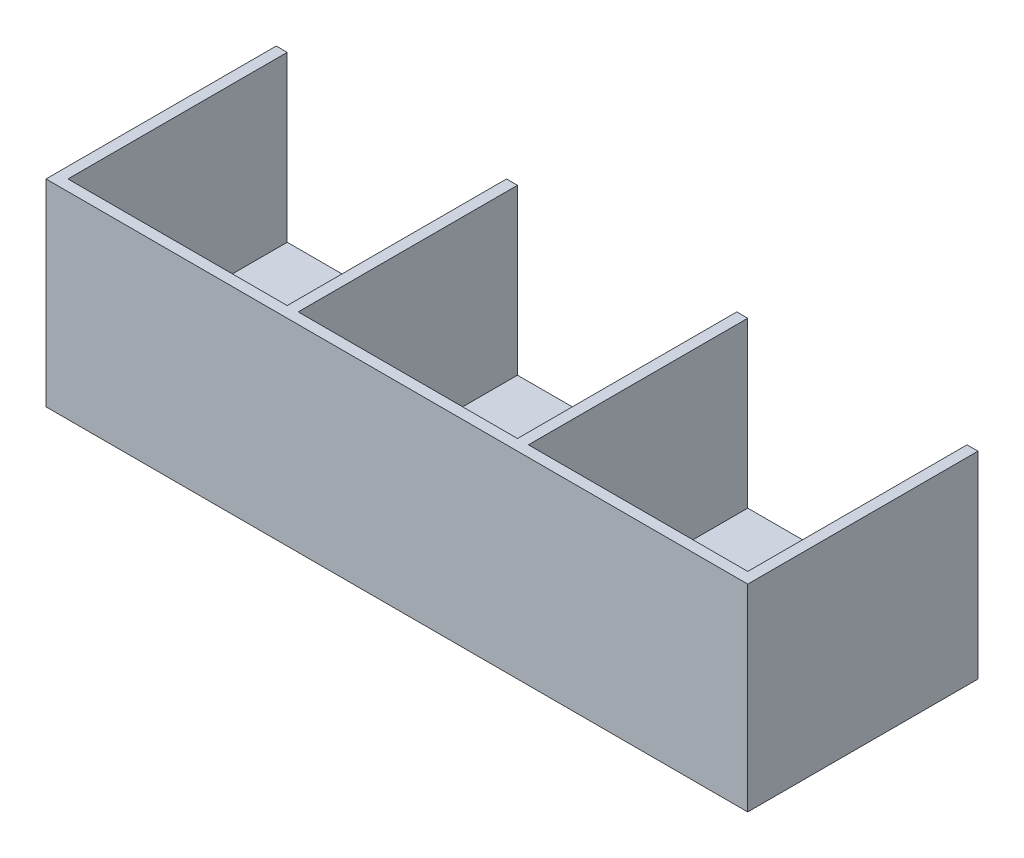
SolidWorks part; units mm, degrees
ref_plane "Alzado" through (0, 0, 0) normal (0, 0, 1) x (1, 0, 0)
ref_plane "Planta" through (0, 0, 0) normal (0, 1, 0) x (1, 0, 0)
ref_plane "Vista lateral" through (0, 0, 0) normal (1, 0, 0) x (0, 0, -1)
sketch "Croquis1" plane through (0, 0, 0) normal (0, 1, 0) x (1, 0, 0)
  line L1 (-320, 110) -> (320, 110)
  line L2 (-320, 110) -> (-320, -110)
  line L3 (-320, -110) -> (320, -110)
  line L4 (320, 110) -> (320, -110)
  line L5 (-310, 100) -> (-110, 100)
  line L6 (-310, 100) -> (-310, -100)
  line L7 (-310, -100) -> (-110, -100)
  line L8 (-110, 100) -> (-110, -100)
  line L9 (-100, 100) -> (100, 100)
  line L10 (-100, 100) -> (-100, -100)
  line L11 (-100, -100) -> (100, -100)
  line L12 (100, 100) -> (100, -100)
  line L13 (110, 100) -> (310, 100)
  line L14 (110, 100) -> (110, -100)
  line L15 (110, -100) -> (310, -100)
  line L16 (310, 100) -> (310, -100)
  point P0 (0, 0)
  dimension "D1" = 640
  dimension "D2" = 220
  dimension "D3" = 200
  dimension "D4" = 200
  dimension "D5" = 200
  dimension "D6" = 10
  dimension "D7" = 10
  dimension "D8" = 10
  dimension "D9" = 10
  dimension "D10" = 10
  dimension "D11" = 10
  dimension "D12" = 200
  dimension "D13" = 200
  dimension "D14" = 200
extrude "Saliente-Extruir1" add sketch "Croquis1" along normal blind 150
sketch "Croquis2" plane through (0, 150, 0) normal (0, 1, 0) x (1, 0, 0)
  line L0 (320, -110) -> (320, 110) construction
  line L1 (-320, -110) -> (320, -110)
  line L2 (-320, -110) -> (-320, -27.2423)
  line L3 (-320, -27.2423) -> (320, -27.2423)
  line L4 (320, -110) -> (320, -27.2423)
sketch "Croquis3" plane through (0, 0, 0) normal (0, -1, 0) x (1, 0, 0)
  line L1 (-320, 110) -> (320, 110)
  line L2 (-320, 110) -> (-320, -110)
  line L3 (-320, -110) -> (320, -110)
  line L4 (320, 110) -> (320, -110)
extrude "Saliente-Extruir3" add sketch "Croquis3" along normal blind 10
sketch "Croquis4" plane through (0, 0, 0) normal (0, 1, 0) x (1, 0, 0)
  line L0 (-310, 100) -> (-310, -100) construction
  line L1 (310, -100) -> (310, 100) construction
  circle A0 centre (-210, 73.4506) radius 4.6265
  circle A1 centre (210, 73.4506) radius 4.6265
  dimension "D1" = 100
  dimension "D2" = 100
extrude "Cortar-Extruir1" cut sketch "Croquis4" against normal through all
sketch "Croquis5" plane through (0, 150, 0) normal (0, 1, 0) x (1, 0, 0)
  line L0 (320, -110) -> (320, 110) construction
  line L1 (-320, 110) -> (320, 110)
  line L2 (-320, 110) -> (-320, 100)
  line L3 (-320, 100) -> (320, 100)
  line L4 (320, 110) -> (320, 100)
  line L5 (310, 100) -> (110, 100) construction
extrude "Cortar-Extruir2" cut sketch "Croquis5" against normal through all
sketch "Croquis6" plane through (0, -10, 0) normal (0, -1, 0) x (1, 0, 0)
  line L1 (-320, 110) -> (320, 110)
  line L2 (-320, 110) -> (-320, -100)
  line L3 (-320, -100) -> (320, -100)
  line L4 (320, 110) -> (320, -100)
extrude "Saliente-Extruir4" add sketch "Croquis6" along normal blind 20
